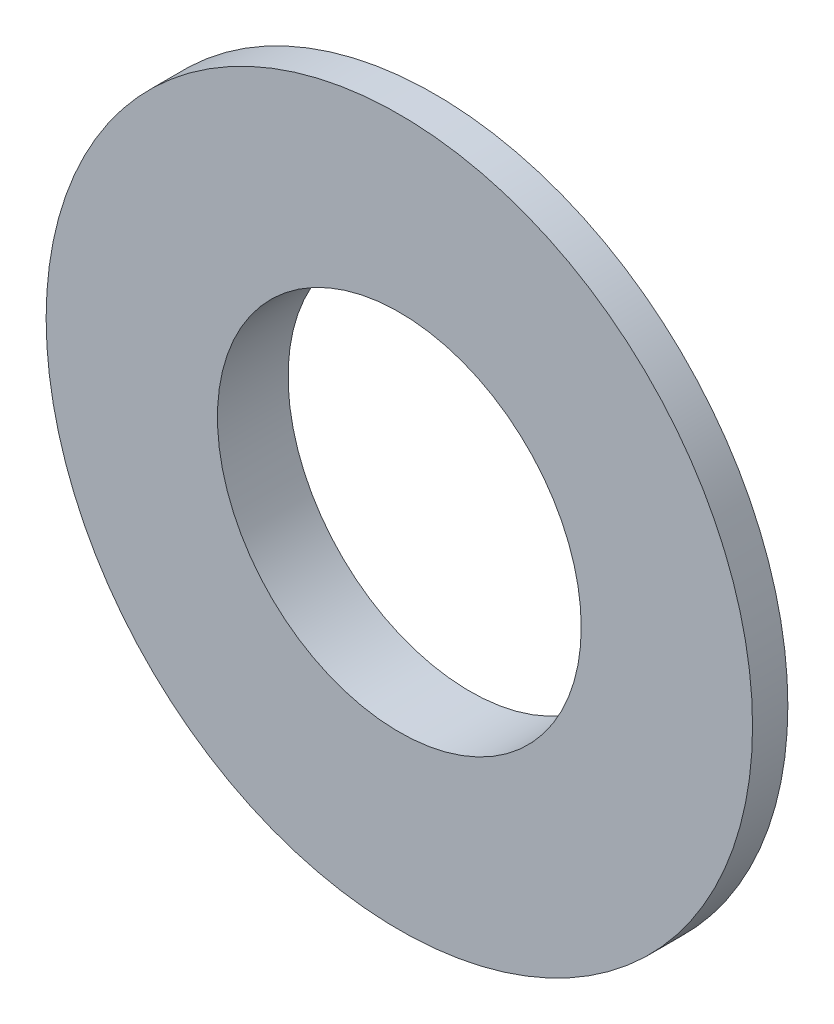
SolidWorks part; units mm, degrees
ref_plane "Plan de face" through (0, 0, 0) normal (0, 0, 1) x (1, 0, 0)
ref_plane "Plan de dessus" through (0, 0, 0) normal (0, 1, 0) x (1, 0, 0)
ref_plane "Plan de droite" through (0, 0, 0) normal (1, 0, 0) x (0, 0, -1)
sketch "Esquisse1" plane through (0, 0, 0) normal (0, 0, 1) x (1, 0, 0)
  circle A0 centre (0, 0) radius 10.3
  circle A1 centre (0, 0) radius 15.7
  dimension "D1" = 20.6
  dimension "D2" = 31.4
extrude "Boss.-Extru.1" add sketch "Esquisse1" along normal blind 2
sketch "Esquisse2" plane through (0, 0, 2) normal (0, 0, 1) x (1, 0, 0)
  circle A0 centre (0, 0) radius 20
  circle A2 centre (0, 0) radius 15.7
  circle A3 centre (0, 0) radius 15.7
  circle M1 centre (0, 0) radius 15.7
  circle M2 centre (0, 0) radius 10.3
  dimension "D1" = 40
  dimension "D2" = 0
extrude "Boss.-Extru.3" add sketch "Esquisse2" along normal blind 2 contours M1 M2 | A0 M1
scale "Echelle1" scale about centroid uniform scaling yes scale factor 2
scale "Echelle2" scale about centroid uniform scaling yes scale factor 0.25
